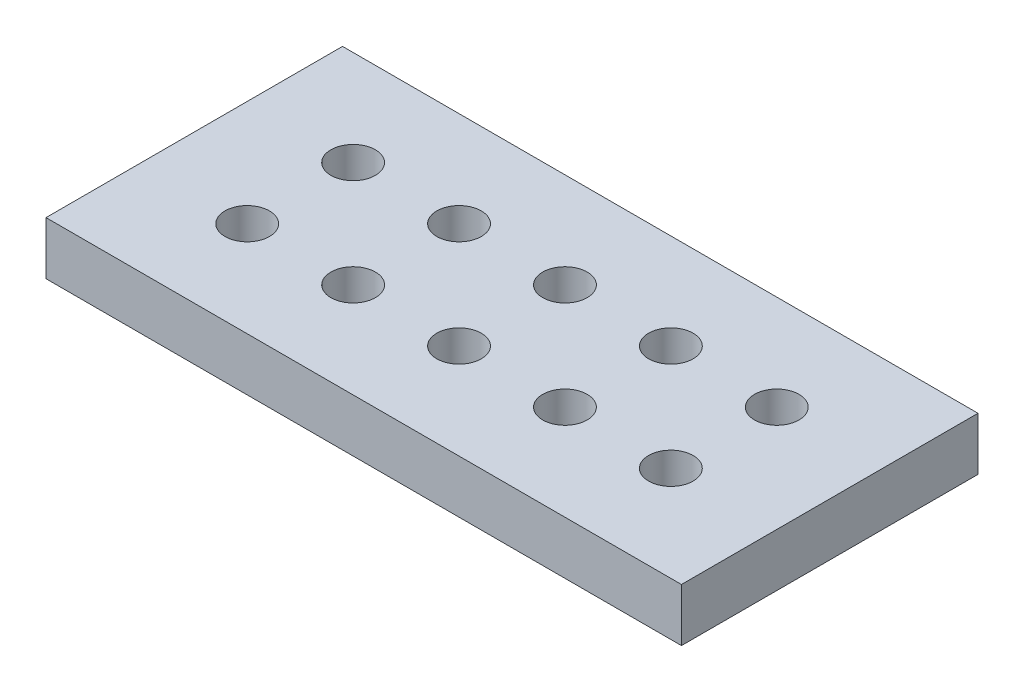
SolidWorks part; units mm, degrees
ref_plane "Front Plane" through (0, 0, 0) normal (0, 0, 1) x (1, 0, 0)
ref_plane "Top Plane" through (0, 0, 0) normal (0, 1, 0) x (1, 0, 0)
ref_plane "Right Plane" through (0, 0, 0) normal (1, 0, 0) x (0, 0, -1)
sketch "Sketch1" plane through (0, 0, 0) normal (0, 1, 0) x (1, 0, 0)
  line L0 (-38.1, 0) -> (38.1, 0) construction
  line L1 (38.1, 17.78) -> (-38.1, 17.78)
  line L2 (38.1, 17.78) -> (38.1, -17.78)
  line L3 (38.1, -17.78) -> (-38.1, -17.78)
  line L4 (-38.1, 17.78) -> (-38.1, -17.78)
  line L5 (38.1, 17.78) -> (-38.1, -17.78) construction
  line L6 (38.1, -17.78) -> (-38.1, 17.78) construction
  circle A0 centre (-25.4, 6.35) radius 2.667
  circle A1 centre (-12.7, 6.35) radius 2.667
  circle A2 centre (0, 6.35) radius 2.667
  circle A3 centre (12.7, 6.35) radius 2.667
  circle A4 centre (25.4, 6.35) radius 2.667
  circle A6 centre (-12.7, -6.35) radius 2.667
  circle A7 centre (0, -6.35) radius 2.667
  circle A8 centre (12.7, -6.35) radius 2.667
  circle A9 centre (25.4, -6.35) radius 2.667
  circle A11 centre (-25.4, -6.35) radius 2.667
  point P0 (0, 0)
  dimension "D3" = 5.334
  dimension "D1" = 35.56
  dimension "D2" = 76.2
  dimension "D4" = 6.35
  dimension "D5" = 12.7
  dimension "D6" = 5
  dimension "D7" = 2
extrude "Boss-Extrude1" add sketch "Sketch1" along normal mid plane 6.35
sketch "Sketch2" plane through (-38.1, 0, 0) normal (-1, 0, 0) x (0, 0, 1)
  circle A0 centre (-12.7, 0) radius 1.3462
  circle A1 centre (-6.35, 0) radius 1.3462
  circle A2 centre (0, 0) radius 1.3462
  circle A3 centre (6.35, 0) radius 1.3462
  circle A4 centre (12.7, 0) radius 1.3462
  dimension "D1" = 2.6924
  dimension "D2" = 12.7
  dimension "D3" = 5
extrude "Cut-Extrude1" cut sketch "Sketch2" against normal blind 6.35
